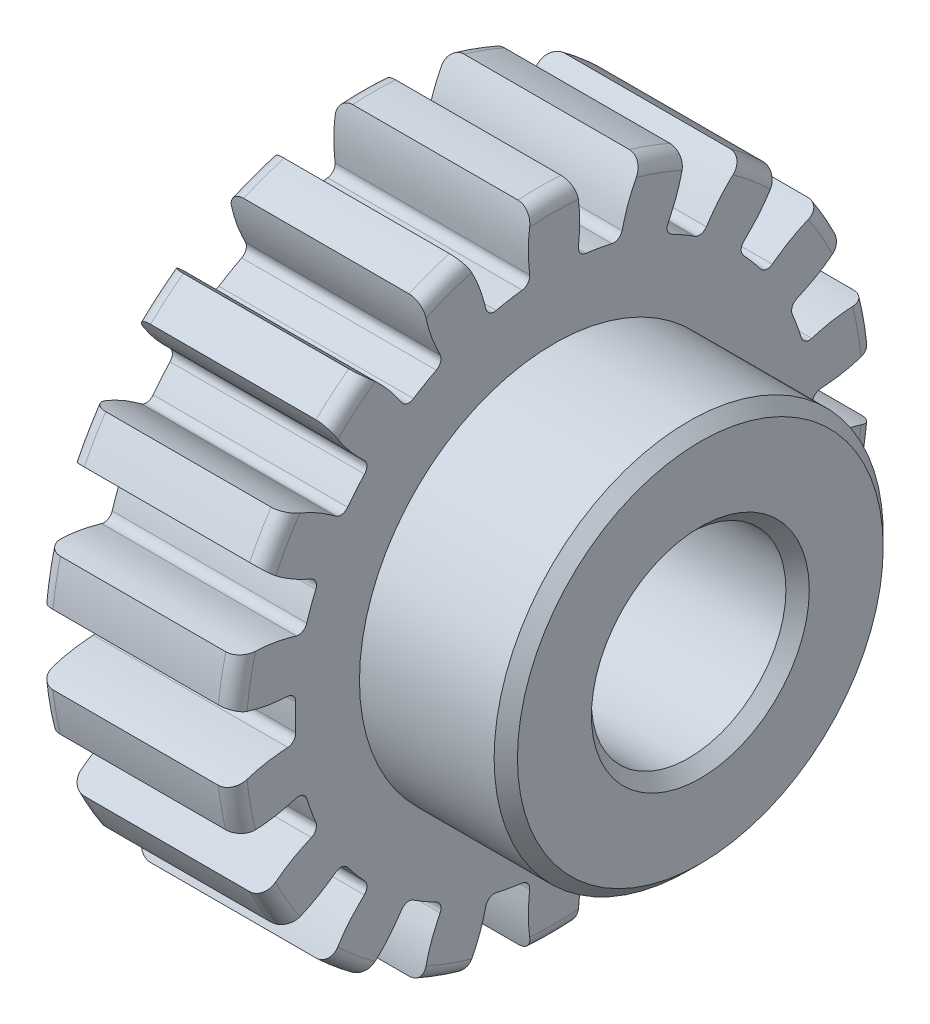
SolidWorks part; units mm, degrees
ref_plane "Front" through (0, 0, 0) normal (0, 0, 1) x (1, 0, 0)
ref_plane "Top" through (0, 0, 0) normal (0, 1, 0) x (1, 0, 0)
ref_plane "Right" through (0, 0, 0) normal (1, 0, 0) x (0, 0, -1)
sketch "Sketch1" plane through (0, 0, 0) normal (0, 0, 1) x (1, 0, 0)
  line L0 (-5.5626, 0) -> (5.5626, 0) construction
  line L1 (-5.5626, 10.541) -> (0.7874, 10.541)
  line L2 (-5.5626, 10.541) -> (-5.5626, 3.175)
  line L3 (-5.5626, 3.175) -> (5.5626, 3.175)
  line L4 (5.5626, 6.35) -> (5.5626, 3.175)
  line L5 (0.7874, 10.541) -> (0.7874, 6.35)
  line L6 (0.7874, 6.35) -> (5.5626, 6.35)
  line L7 (3.175, 6.35) -> (3.175, 3.175) construction
  point P12 (3.175, 6.35)
  point P14 (5.5626, -6.35)
  point P15 (-5.5626, -10.541)
  dimension "Hub Diameter" = 12.7
  dimension "Hub Width" = 4.7752
  dimension "OD" = 21.082
  dimension "Overall Width" = 11.1252
  dimension "For Shaft Diameter" = 6.35
  dimension "Face Width" = 6.35
  dimension "D1" = 11.1252
sketch "Sketch2" plane through (0, 0, 0) normal (1, 0, 0) x (0, 0, -1)
  line L0 (0, 0) -> (0, 9.525) construction
  circle A0 centre (0, 0) radius 9.525 construction
  circle A1 centre (0, 0) radius 3.175 construction
  point P3 (3.2577, 8.9506)
  point P5 (6.1226, 7.2966)
  point P7 (0, -9.525)
  point P8 (-3.2577, -8.9506)
  point P9 (8.2489, 4.7625)
  point P10 (9.3803, 1.654)
  point P11 (-6.1226, -7.2966)
  point P12 (-8.2489, -4.7625)
  point P13 (-9.3803, -1.654)
  point P14 (-9.3803, 1.654)
  point P15 (-8.2489, 4.7625)
  point P16 (-6.1226, 7.2966)
  point P17 (-3.2577, 8.9506)
  point P18 (0, 9.525)
  point P19 (9.3803, -1.654)
  point P20 (8.2489, -4.7625)
  point P21 (6.1226, -7.2966)
  point P22 (3.2577, -8.9506)
  point P26 (0, 0)
  dimension "Number of Teeth" = 18
sketch "Sketch12" plane through (0, 0, 0) normal (0, 0, 1) x (1, 0, 0)
  line L0 (-5.5626, 10.541) -> (-5.5626, 3.175) construction
  line L1 (-5.5626, 10.541) -> (0.7874, 10.541) construction
  line L2 (0.7874, 10.541) -> (0.7874, 6.35) construction
  line L3 (0.7874, 6.35) -> (5.5626, 6.35) construction
  line L4 (5.5626, 6.35) -> (5.5626, 3.175) construction
  line L5 (-5.5626, 3.175) -> (5.5626, 3.175) construction
  line L6 (-5.5626, 10.541) -> (-5.5626, 3.175)
  line L7 (-5.5626, 10.541) -> (0.7874, 10.541)
  line L8 (0.7874, 10.541) -> (0.7874, 6.35)
  line L9 (0.7874, 6.35) -> (5.5626, 6.35)
  line L10 (5.5626, 6.35) -> (5.5626, 3.175)
  line L11 (-5.5626, 3.175) -> (5.5626, 3.175)
  line L12 (0, 0) -> (5.5626, 0) construction
revolve "Revolve3" add sketch "Sketch12" angle 360 about L12
sketch "Sketch6" plane through (-5.5626, 0, 0) normal (-1, 0, 0) x (0, 0, -1)
  line L0 (-8.953, 0.7462) -> (-9.4921, 0.7911) construction
  line L1 (0, 0) -> (-8.4432, 0) construction
  line L2 (-9.4921, 0.7911) -> (-14.7932, 2.6439) construction
  line L3 (0, 0) -> (-10.3809, -1.8304) construction
  line L4 (-14.7932, 2.6439) -> (-14.7932, -2.6439) construction
  line L5 (-14.7932, -2.6439) -> (-9.4921, -0.7911) construction
  line L6 (-9.4921, -0.7911) -> (-8.953, -0.7462) construction
  line L7 (-8.4432, 0) -> (-10.541, 0) construction
  line L8 (-8.414, -0.7013) -> (-8.414, 0.7013) construction
  line L9 (-8.414, -0.7013) -> (-8.953, -0.7462)
  line L10 (-8.414, 0.7013) -> (-8.953, 0.7462)
  line L11 (-9.4921, -0.7911) -> (-9.4921, 0.7911) construction
  line L12 (-8.414, -0.7013) -> (-9.4921, -0.7013) construction
  circle A0 centre (0, 0) radius 9.525 construction
  circle A1 centre (0, 0) radius 8.4432 construction
  arc A2 (-8.414, 0.7013) -> (-8.414, -0.7013) centre (0, 0) ccw
  circle A4 centre (0, 0) radius 10.541 construction
  circle A6 centre (0, 0) radius 10.541 construction
  arc A7 (-10.2362, -2.5165) -> (-10.4796, -1.1363) centre (0, 0) cw construction
  arc A8 (-10.4796, -1.1363) -> (-8.953, -0.7462) centre (-8.5594, -5.4689) cw
  arc A9 (-8.953, 0.7462) -> (-10.4796, 1.1363) centre (-8.5594, 5.4689) cw
  arc A10 (-10.4796, 1.1363) -> (-10.4796, -1.1363) centre (0, 0) ccw
  point P1 (-8.953, -0.7013)
  point P7 (-9.4921, 0)
  point P21 (-8.414, -0.7013)
  point P24 (-8.414, 0.7013)
  point P32 (-9.4921, 0)
  dimension "D4" = 6.35
  dimension "D2" = 10
  dimension "D3" = 14.5
  dimension "D1" = 1.4026
sketch "Sketch7" plane through (0, 0, 0) normal (0, 0, 1) x (1, 0, 0)
  line L0 (-5.5626, 0) -> (0.7874, 0)
  line L3 (-5.5626, 0) -> (5.5626, 0) construction
fillet "Fillet1" radius 0.4762 2 edges at (0.7874, 0, 10.541) (-5.5626, 0, 10.541)
sweep "Cut-Sweep1" cut profiles "Sketch6" path "Sketch7" parameters "D1"=0
fillet "Fillet2" radius 0.2805 2 edges
pattern_circular "CirPattern4" count 18 over 360 about axis through (-5.5626, 0, 0) along (1, 0, 0) of "Cut-Sweep1", "Fillet2"
chamfer "Chamfer1" distance 0.381 angle 45 3 edges at (5.5626, 0, 3.175) (5.5626, 0, 6.35) (-5.5626, 0, 3.175)
ref_plane "Plane1" through (-2.2606, 0, 0) normal (1, 0, 0) x (0, 0, -1)
sketch "Sketch15" plane through (-2.2606, 0, 0) normal (1, 0, 0) x (0, 0, -1)
  circle A0 centre (0, 0) radius 9.779
  dimension "D1" = 19.558
equation "\"D1@CirPattern4\" = \"Number of Teeth@Sketch2\""
equation "\"D1@Sketch2\" = \"For Shaft Diameter@Sketch1\""
equation "\"D2@Sketch6\"=360 / \"Number of Teeth@Sketch2\"/2"
equation "\"D1@Fillet1\" = \"Face Width@Sketch1\" * 0.075"
equation "\"D1@Chamfer1\" = \"For Shaft Diameter@Sketch1\" * 0.06"
equation "\"D1@Fillet2\"=\"D1@Sketch6\"/5"
